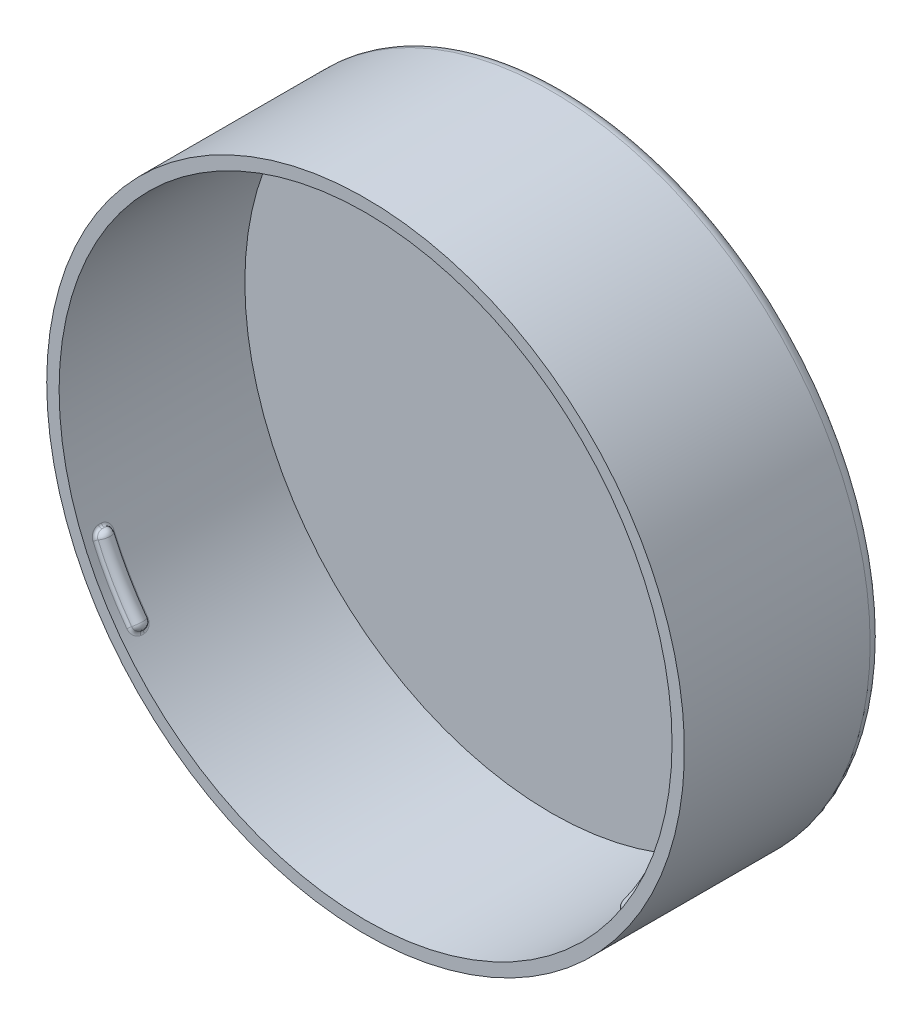
SolidWorks part; units mm, degrees
ref_plane "Front Plane" through (0, 0, 0) normal (1, 0, 0) x (0, 1, 0)
ref_plane "Top Plane" through (0, 0, 0) normal (0, 0, 1) x (0, 1, 0)
ref_plane "Right Plane" through (0, 0, 0) normal (0, 1, 0) x (-1, 0, 0)
sketch "Sketch1" plane through (0, 0, 0) normal (1, 0, 0) x (0, 1, 0)
  line L0 (0, 0) -> (-49.5, 0)
  line L1 (-49.5, 0) -> (-49.5, 30)
  line L2 (-49.5, 30) -> (-51.5, 30)
  line L3 (-51.5, 30) -> (-51.5, -2)
  line L4 (-51.5, -2) -> (0, -2)
  line L5 (0, -2) -> (0, 0)
  dimension "D1" = 2
  dimension "D2" = 49.5
  dimension "D3" = 2
  dimension "D4" = 30
revolve "Revolve1" add sketch "Sketch1" angle 360 about L5
ref_axis "Axis1" through (0, 0, 30) along (0, 0, -1)
fillet "Fillet1" radius 2 1 edges at (-51.5, 0, -2)
sketch "Sketch2" [suppressed] plane through (0, 0, 0) normal (0, 1, 0) x (-1, 0, 0)
  line L0 (-26.5919, 0) -> (-36.004, 20.1843)
  line L1 (-51.5, 0) -> (51.5, 0) construction
  line L2 (-36.004, 20.1843) -> (-36.004, 45)
  line L3 (-36.004, 45) -> (-38, 45)
  line L4 (-38, 43) -> (-38, 15)
  line L5 (-38, 15) -> (-31.0054, 0)
  line L6 (-26.5919, 0) -> (-31.0054, 0)
  line L7 (51.5, 20) -> (-51.5, 20) construction
  line L8 (-38, 45) -> (-38, 43) construction
  line L9 (-36.004, 20.1843) -> (-38, 15) construction
  arc A0 (-38, 45) -> (-38, 43) centre (-38, 44) ccw
  dimension "D7" = 1
  dimension "D1" = 1.996
  dimension "D2" = 25
  dimension "D3" = 38
  dimension "D4" = 4
  dimension "D5" = 15
  dimension "D6" = 155
extrude "Boss-Extrude1" [suppressed] add sketch "Sketch2" along normal mid plane 12
fillet "Fillet2" [suppressed] radius 5
fillet "Fillet4" [suppressed] radius 15
chamfer "Chamfer1" [suppressed] distance 1 angle 65
mirror "Mirror2" [suppressed] about plane through (0, 0, 0) normal (1, 0, 0)
fillet "Fillet5" [suppressed] radius 5
sketch "Sketch3" plane through (0, 0, 0) normal (1, 0, 0) x (0, 1, 0)
  line L0 (78.2161, 30) -> (-78.2161, 30) construction
  line L2 (49.5014, 28.25) -> (49.5014, 25.75)
  arc A0 (49.5014, 28.25) -> (49.5014, 25.75) centre (49.5014, 27) ccw
  point P3 (49.5014, 29.1505)
  point P6 (0, 0)
  dimension "D1" = 3
  dimension "D2" = 49.5014
  dimension "D3" = 2.5
revolve "Revolve2" add sketch "Sketch3" angle 15 mid plane about axis through (0, 0, 30) along (0, 0, -1)
fillet "Fillet9" radius 1 2 edges at (-6.2981, 47.8386, 27) (6.2981, 47.8386, 27)
fillet "Fillet10" radius 0.5 8 edges at (6.0887, 49.1241, 28.0309) (6.2437, 49.1046, 26.1253) (6.461, 49.0765, 27) (0, 49.5, 28.25) (0, 49.5, 25.75) (-6.0887, 49.1241, 25.9691) (-6.2437, 49.1046, 27.8747) (-6.461, 49.0765, 27)
pattern_circular "CirPattern2" count 3 over 360 about axis through (0, 0, 30) along (0, 0, -1) of "Revolve2", "Fillet9", "Fillet10"
